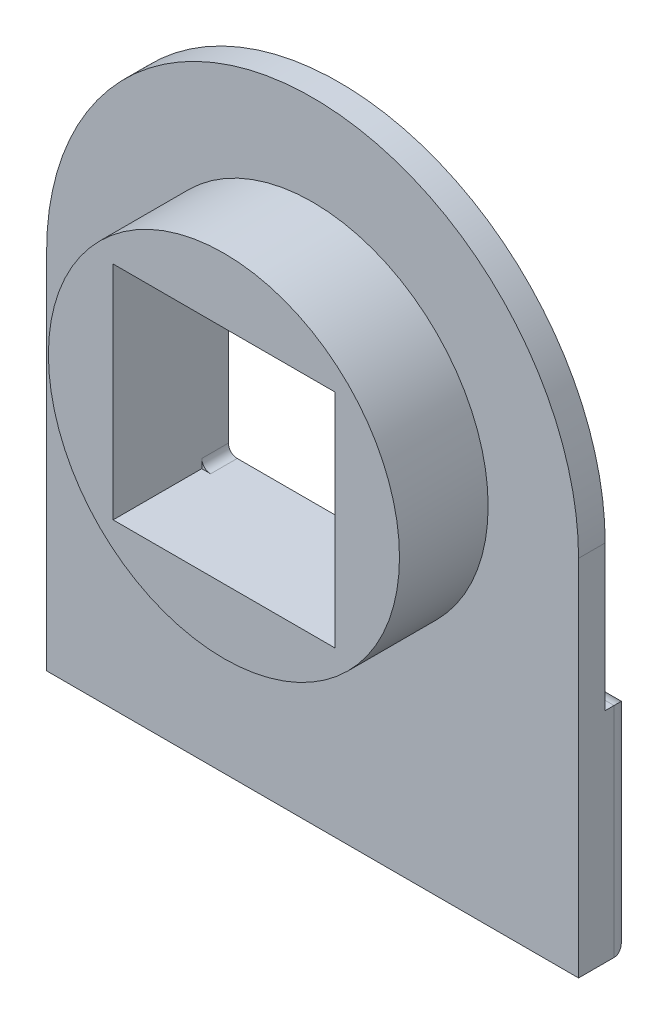
SolidWorks part; units mm, degrees
ref_plane "前视基准面" through (0, 0, 0) normal (0, 0, 1) x (1, 0, 0)
ref_plane "上视基准面" through (0, 0, 0) normal (0, 1, 0) x (1, 0, 0)
ref_plane "右视基准面" through (0, 0, 0) normal (1, 0, 0) x (0, 0, -1)
sketch "草图1" plane through (0, 0, 0) normal (0, 0, 1) x (1, 0, 0)
  line L0 (0, -12.5) -> (12.5, -12.5)
  line L1 (12.5, -12.5) -> (12.5, 12.5)
  line L2 (12.5, 12.5) -> (0, 12.5)
  line L3 (0, 12.5) -> (-12.5, 12.5)
  line L4 (-12.5, 12.5) -> (-12.5, -12.5)
  line L5 (-12.5, -12.5) -> (0, -12.5)
  circle A0 centre (0, 0) radius 19.8
  point P3 (0, 12.5)
  point P4 (0, -12.5)
  dimension "D1" = 12.5
  dimension "D3" = 39.6
  dimension "D2" = 12.5
  dimension "D4" = 25
  dimension "D5" = 25
extrude "凸台-拉伸1" add sketch "草图1" along normal blind 13
sketch "草图2" plane through (0, 0, 0) normal (0, 0, -1) x (-1, 0, 0)
  line L1 (-11.5, -12.5) -> (11.5, -12.5)
  line L2 (-12.5, -11.5) -> (-12.5, 11.5)
  line L3 (-11.5, 12.5) -> (11.5, 12.5)
  line L4 (12.5, -11.5) -> (12.5, 11.5)
  line L5 (-12.5, -12.5) -> (12.5, 12.5) construction
  line L6 (-12.5, 12.5) -> (12.5, -12.5) construction
  line L7 (-30, -41) -> (30, -41)
  line L8 (-30, -41) -> (-30, 0)
  line L9 (-30, 0) -> (30, 0)
  line L10 (30, -41) -> (30, 0)
  line L11 (-30, -41) -> (30, 0) construction
  line L12 (-30, 0) -> (30, -41) construction
  circle A0 centre (0, 0) radius 30
  arc A1 (11.5, 12.5) -> (12.5, 11.5) centre (11.5, 11.5) cw
  arc A2 (11.5, -12.5) -> (12.5, -11.5) centre (11.5, -11.5) ccw
  arc A3 (-11.5, -12.5) -> (-12.5, -11.5) centre (-11.5, -11.5) cw
  arc A4 (-12.5, 11.5) -> (-11.5, 12.5) centre (-11.5, 11.5) cw
  point P7 (0, -20.5)
  circle M2 centre (0, 0) radius 19.8
  line M3 (12.5, -12.5) -> (-12.5, -12.5)
  line M4 (-12.5, -12.5) -> (-12.5, 12.5)
  line M5 (-12.5, 12.5) -> (12.5, 12.5)
  line M6 (12.5, 12.5) -> (12.5, -12.5)
  dimension "D1" = 60
  dimension "D2" = 41
  dimension "D3" = 1
extrude "凸台-拉伸2" add sketch "草图2" against normal blind 3 contours L9 A0 M2 | L9 A0 M2 | L9 L2 M2 M5 M6 | L9 L4 M2 M3 M4 | A0 L8 L7 L10 | A4 M4 M5 | A1 M5 M6 | A3 M3 M4 | A2 M3 M6
sketch "草图3" plane through (0, 0, 0) normal (0, 0, -1) x (-1, 0, 0)
  line L1 (-30, -16.3816) -> (30, -16.3816)
  line L2 (-30, -16.3816) -> (-30, -41)
  line L3 (-30, -41) -> (30, -41)
  line L4 (30, -16.3816) -> (30, -41)
extrude "凸台-拉伸3" add sketch "草图3" along normal blind 3
fillet "圆角1" radius 2 4 edges at (0, -16.3816, -3) (-30, -28.6908, -3) (0, -41, -3) (30, -28.6908, -3)
sketch "草图4" plane through (0, 0, 0) normal (0, 0, -1) x (-1, 0, 0)
  circle A0 centre (20.3393, -11.208) radius 1.8217
extrude "切除-拉伸1" cut sketch "草图4" along normal blind 10 and the other way blind 10
